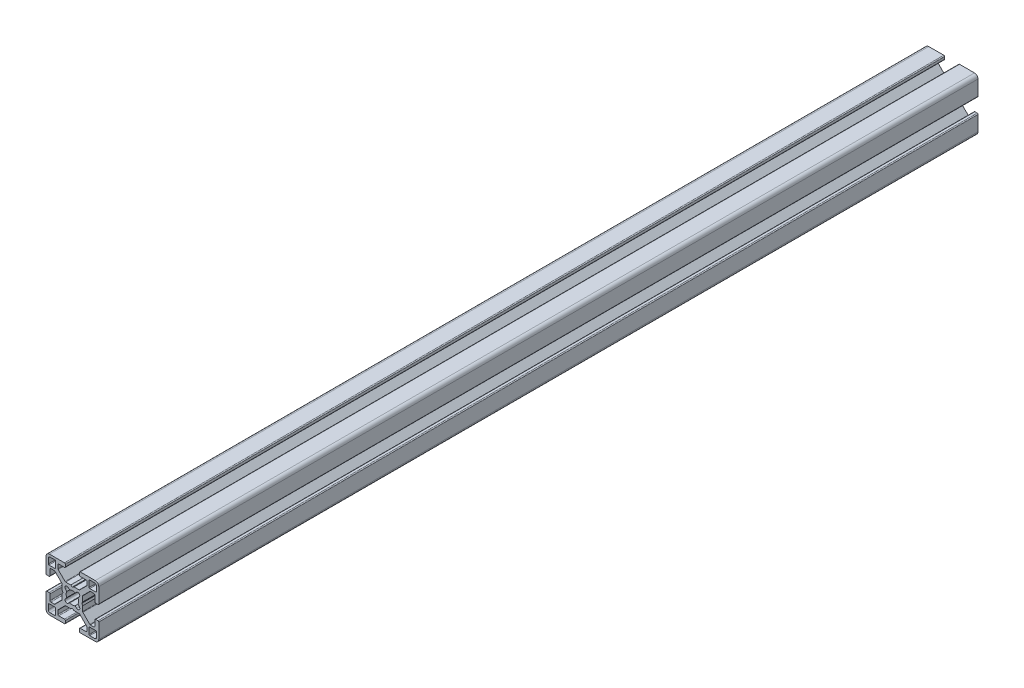
SolidWorks part; units mm, degrees
material "6105-T5 Aluminum"
ref_plane "Front Plane" through (0, 0, 0) normal (0, 0, 1) x (1, 0, 0)
ref_plane "Top Plane" through (0, 0, 0) normal (0, 1, 0) x (1, 0, 0)
ref_plane "Right Plane" through (0, 0, 0) normal (1, 0, 0) x (0, 0, -1)
sketch "Sketch1" plane through (0, 0, 0) normal (0, 0, 1) x (1, 0, 0)
  line L0 (9.5, -13.3189) -> (9.5, -9.88)
  line L1 (9.88, -9.5) -> (13.3189, -9.5)
  line L2 (13.6999, -9.881) -> (13.6999, -12.6999)
  line L3 (12.6999, -13.6999) -> (9.881, -13.6999)
  line L4 (-13.3189, -9.5) -> (-9.88, -9.5)
  line L5 (-9.5, -9.88) -> (-9.5, -13.3189)
  line L6 (-9.881, -13.6999) -> (-12.6999, -13.6999)
  line L7 (-13.6999, -12.6999) -> (-13.6999, -9.881)
  line L8 (-1.4942, -3.1981) -> (-2.4733, -3.9799)
  line L9 (-3.9799, -2.4733) -> (-3.1981, -1.4942)
  line L10 (-3.1981, 1.4942) -> (-3.9799, 2.4733)
  line L11 (-2.4733, 3.9799) -> (-1.4942, 3.1981)
  line L12 (1.4942, 3.1981) -> (2.4733, 3.9799)
  line L13 (3.9799, 2.4733) -> (3.1981, 1.4942)
  line L14 (3.1981, -1.4942) -> (3.9799, -2.4733)
  line L15 (2.4733, -3.9799) -> (1.4942, -3.1981)
  line L16 (-9.5, 13.3189) -> (-9.5, 9.88)
  line L17 (-9.88, 9.5) -> (-13.3189, 9.5)
  line L18 (-13.6999, 9.881) -> (-13.6999, 12.6999)
  line L19 (-12.6999, 13.6999) -> (-9.881, 13.6999)
  line L20 (9.881, 13.6999) -> (12.6999, 13.6999)
  line L21 (13.6999, 12.6999) -> (13.6999, 9.881)
  line L22 (13.3189, 9.5) -> (9.88, 9.5)
  line L23 (9.5, 9.88) -> (9.5, 13.3189)
  line L24 (12.7425, -4.5) -> (12.7425, -7.7325)
  line L25 (12.2428, -8.25) -> (10.2602, -8.25)
  line L26 (9.9066, -8.1035) -> (5.9811, -4.178)
  line L27 (5.8347, -3.8245) -> (5.8347, -1.0125)
  line L28 (5.8347, -1.0125) -> (5.3247, -0.0625)
  line L29 (5.3247, -0.0625) -> (5.8347, 0.8875)
  line L30 (5.8347, 0.8875) -> (5.8347, 3.8245)
  line L31 (5.9811, 4.178) -> (9.9066, 8.1035)
  line L32 (10.2602, 8.25) -> (12.2428, 8.25)
  line L33 (12.7425, 7.7325) -> (12.7425, 4.5)
  line L34 (13.2425, 4) -> (14.4999, 4)
  line L35 (14.9999, 4.5) -> (14.9999, 12.9999)
  line L36 (12.9999, 14.9999) -> (4.5, 14.9999)
  line L37 (4, 14.4999) -> (4, 13.2425)
  line L38 (4.5, 12.7425) -> (7.7325, 12.7425)
  line L39 (8.25, 12.2428) -> (8.25, 10.2602)
  line L40 (8.1035, 9.9066) -> (4.178, 5.9811)
  line L41 (3.8245, 5.8347) -> (0.95, 5.8347)
  line L42 (0.95, 5.8347) -> (0, 5.3247)
  line L43 (0, 5.3247) -> (-0.95, 5.8347)
  line L44 (-0.95, 5.8347) -> (-3.8245, 5.8347)
  line L45 (-4.178, 5.9811) -> (-8.1035, 9.9066)
  line L46 (-8.25, 10.2602) -> (-8.25, 12.2428)
  line L47 (-7.7325, 12.7425) -> (-4.5, 12.7425)
  line L48 (-4, 13.2425) -> (-4, 14.4999)
  line L49 (-4.5, 14.9999) -> (-12.9999, 14.9999)
  line L50 (-14.9999, 12.9999) -> (-14.9999, 4.5)
  line L51 (-14.4999, 4) -> (-13.2425, 4)
  line L52 (-12.7425, 4.5) -> (-12.7425, 7.7325)
  line L53 (-12.2428, 8.25) -> (-10.2602, 8.25)
  line L54 (-9.9066, 8.1035) -> (-5.9811, 4.178)
  line L55 (-5.8347, 3.8245) -> (-5.8347, 0.8875)
  line L56 (-5.8347, 0.8875) -> (-5.3247, -0.0625)
  line L57 (-5.3247, -0.0625) -> (-5.8347, -1.0125)
  line L58 (-5.8347, -1.0125) -> (-5.8347, -3.8245)
  line L59 (-5.9811, -4.178) -> (-9.9066, -8.1035)
  line L60 (-10.2602, -8.25) -> (-12.2428, -8.25)
  line L61 (-12.7425, -7.7325) -> (-12.7425, -4.5)
  line L62 (-13.2425, -4) -> (-14.4999, -4)
  line L63 (-14.9999, -4.5) -> (-14.9999, -12.9999)
  line L64 (-12.9999, -14.9999) -> (-4.5, -14.9999)
  line L65 (-4, -14.4999) -> (-4, -13.2425)
  line L66 (-4.5, -12.7425) -> (-7.7325, -12.7425)
  line L67 (-8.25, -12.2428) -> (-8.25, -10.2602)
  line L68 (-8.1035, -9.9066) -> (-4.178, -5.9811)
  line L69 (-3.8245, -5.8347) -> (-0.95, -5.8347)
  line L70 (-0.95, -5.8347) -> (0, -5.3247)
  line L71 (0, -5.3247) -> (0.95, -5.8347)
  line L72 (0.95, -5.8347) -> (3.8245, -5.8347)
  line L73 (4.178, -5.9811) -> (8.1035, -9.9066)
  line L74 (8.25, -10.2602) -> (8.25, -12.2428)
  line L75 (7.7325, -12.7425) -> (4.5, -12.7425)
  line L76 (4, -13.2425) -> (4, -14.4999)
  line L77 (4.5, -14.9999) -> (12.9999, -14.9999)
  line L78 (14.9999, -12.9999) -> (14.9999, -4.5)
  line L79 (14.4999, -4) -> (13.2425, -4)
  arc A0 (9.5, -13.3189) -> (9.881, -13.6999) centre (9.881, -13.3189) ccw
  arc A1 (9.88, -9.5) -> (9.5, -9.88) centre (9.88, -9.88) ccw
  arc A2 (13.6999, -9.881) -> (13.3189, -9.5) centre (13.3189, -9.881) ccw
  arc A3 (12.6999, -13.6999) -> (13.6999, -12.6999) centre (12.6999, -12.6999) ccw
  arc A4 (-13.3189, -9.5) -> (-13.6999, -9.881) centre (-13.3189, -9.881) ccw
  arc A5 (-9.5, -9.88) -> (-9.88, -9.5) centre (-9.88, -9.88) ccw
  arc A6 (-9.881, -13.6999) -> (-9.5, -13.3189) centre (-9.881, -13.3189) ccw
  arc A7 (-13.6999, -12.6999) -> (-12.6999, -13.6999) centre (-12.6999, -12.6999) ccw
  arc A8 (-1.4942, -3.1981) -> (1.4942, -3.1981) centre (0, 0) ccw
  arc A9 (-3.9799, -2.4733) -> (-2.4733, -3.9799) centre (-3.1422, -3.1422) ccw
  arc A10 (-3.1981, 1.4942) -> (-3.1981, -1.4942) centre (0, 0) ccw
  arc A11 (-2.4733, 3.9799) -> (-3.9799, 2.4733) centre (-3.1422, 3.1422) ccw
  arc A12 (1.4942, 3.1981) -> (-1.4942, 3.1981) centre (0, 0) ccw
  arc A13 (3.9799, 2.4733) -> (2.4733, 3.9799) centre (3.1422, 3.1422) ccw
  arc A14 (3.1981, -1.4942) -> (3.1981, 1.4942) centre (0, 0) ccw
  arc A15 (2.4733, -3.9799) -> (3.9799, -2.4733) centre (3.1422, -3.1422) ccw
  arc A16 (-9.5, 13.3189) -> (-9.881, 13.6999) centre (-9.881, 13.3189) ccw
  arc A17 (-9.88, 9.5) -> (-9.5, 9.88) centre (-9.88, 9.88) ccw
  arc A18 (-13.6999, 9.881) -> (-13.3189, 9.5) centre (-13.3189, 9.881) ccw
  arc A19 (-12.6999, 13.6999) -> (-13.6999, 12.6999) centre (-12.6999, 12.6999) ccw
  arc A20 (9.881, 13.6999) -> (9.5, 13.3189) centre (9.881, 13.3189) ccw
  arc A21 (13.6999, 12.6999) -> (12.6999, 13.6999) centre (12.6999, 12.6999) ccw
  arc A22 (13.3189, 9.5) -> (13.6999, 9.881) centre (13.3189, 9.881) ccw
  arc A23 (9.5, 9.88) -> (9.88, 9.5) centre (9.88, 9.88) ccw
  arc A24 (13.2425, -4) -> (12.7425, -4.5) centre (13.2425, -4.5) ccw
  arc A25 (12.2428, -8.25) -> (12.7425, -7.7325) centre (12.2428, -7.75) ccw
  arc A26 (9.9066, -8.1035) -> (10.2602, -8.25) centre (10.2602, -7.75) ccw
  arc A27 (5.8347, -3.8245) -> (5.9811, -4.178) centre (6.3347, -3.8245) ccw
  arc A28 (5.9811, 4.178) -> (5.8347, 3.8245) centre (6.3347, 3.8245) ccw
  arc A29 (10.2602, 8.25) -> (9.9066, 8.1035) centre (10.2602, 7.75) ccw
  arc A30 (12.7425, 7.7325) -> (12.2428, 8.25) centre (12.2428, 7.75) ccw
  arc A31 (12.7425, 4.5) -> (13.2425, 4) centre (13.2425, 4.5) ccw
  arc A32 (14.4999, 4) -> (14.9999, 4.5) centre (14.4999, 4.5) ccw
  arc A33 (14.9999, 12.9999) -> (12.9999, 14.9999) centre (12.9999, 12.9999) ccw
  arc A34 (4.5, 14.9999) -> (4, 14.4999) centre (4.5, 14.4999) ccw
  arc A35 (4, 13.2425) -> (4.5, 12.7425) centre (4.5, 13.2425) ccw
  arc A36 (8.25, 12.2428) -> (7.7325, 12.7425) centre (7.75, 12.2428) ccw
  arc A37 (8.1035, 9.9066) -> (8.25, 10.2602) centre (7.75, 10.2602) ccw
  arc A38 (3.8245, 5.8347) -> (4.178, 5.9811) centre (3.8245, 6.3347) ccw
  arc A39 (-4.178, 5.9811) -> (-3.8245, 5.8347) centre (-3.8245, 6.3347) ccw
  arc A40 (-8.25, 10.2602) -> (-8.1035, 9.9066) centre (-7.75, 10.2602) ccw
  arc A41 (-7.7325, 12.7425) -> (-8.25, 12.2428) centre (-7.75, 12.2428) ccw
  arc A42 (-4.5, 12.7425) -> (-4, 13.2425) centre (-4.5, 13.2425) ccw
  arc A43 (-4, 14.4999) -> (-4.5, 14.9999) centre (-4.5, 14.4999) ccw
  arc A44 (-12.9999, 14.9999) -> (-14.9999, 12.9999) centre (-12.9999, 12.9999) ccw
  arc A45 (-14.9999, 4.5) -> (-14.4999, 4) centre (-14.4999, 4.5) ccw
  arc A46 (-13.2425, 4) -> (-12.7425, 4.5) centre (-13.2425, 4.5) ccw
  arc A47 (-12.2428, 8.25) -> (-12.7425, 7.7325) centre (-12.2428, 7.75) ccw
  arc A48 (-9.9066, 8.1035) -> (-10.2602, 8.25) centre (-10.2602, 7.75) ccw
  arc A49 (-5.8347, 3.8245) -> (-5.9811, 4.178) centre (-6.3347, 3.8245) ccw
  arc A50 (-5.9811, -4.178) -> (-5.8347, -3.8245) centre (-6.3347, -3.8245) ccw
  arc A51 (-10.2602, -8.25) -> (-9.9066, -8.1035) centre (-10.2602, -7.75) ccw
  arc A52 (-12.7425, -7.7325) -> (-12.2428, -8.25) centre (-12.2428, -7.75) ccw
  arc A53 (-12.7425, -4.5) -> (-13.2425, -4) centre (-13.2425, -4.5) ccw
  arc A54 (-14.4999, -4) -> (-14.9999, -4.5) centre (-14.4999, -4.5) ccw
  arc A55 (-14.9999, -12.9999) -> (-12.9999, -14.9999) centre (-12.9999, -12.9999) ccw
  arc A56 (-4.5, -14.9999) -> (-4, -14.4999) centre (-4.5, -14.4999) ccw
  arc A57 (-4, -13.2425) -> (-4.5, -12.7425) centre (-4.5, -13.2425) ccw
  arc A58 (-8.25, -12.2428) -> (-7.7325, -12.7425) centre (-7.75, -12.2428) ccw
  arc A59 (-8.1035, -9.9066) -> (-8.25, -10.2602) centre (-7.75, -10.2602) ccw
  arc A60 (-3.8245, -5.8347) -> (-4.178, -5.9811) centre (-3.8245, -6.3347) ccw
  arc A61 (4.178, -5.9811) -> (3.8245, -5.8347) centre (3.8245, -6.3347) ccw
  arc A62 (8.25, -10.2602) -> (8.1035, -9.9066) centre (7.75, -10.2602) ccw
  arc A63 (7.7325, -12.7425) -> (8.25, -12.2428) centre (7.75, -12.2428) ccw
  arc A64 (4.5, -12.7425) -> (4, -13.2425) centre (4.5, -13.2425) ccw
  arc A65 (4, -14.4999) -> (4.5, -14.9999) centre (4.5, -14.4999) ccw
  arc A66 (12.9999, -14.9999) -> (14.9999, -12.9999) centre (12.9999, -12.9999) ccw
  arc A67 (14.9999, -4.5) -> (14.4999, -4) centre (14.4999, -4.5) ccw
extrude "Extrude1" add sketch "Sketch1" against normal blind 500
